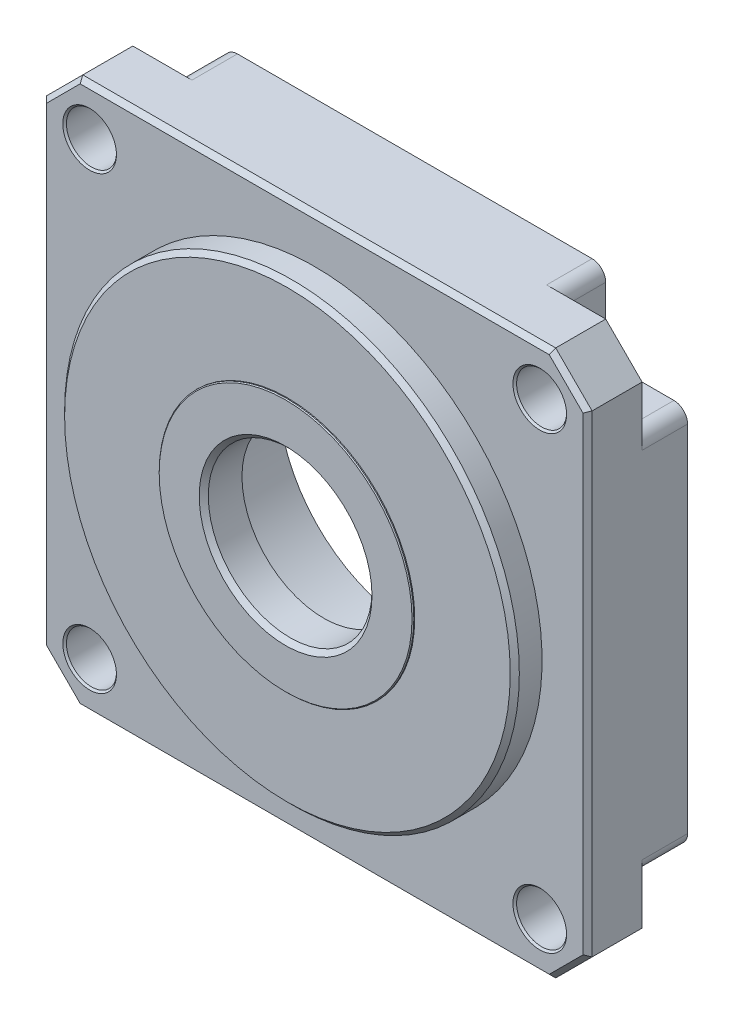
SolidWorks part; units mm, degrees
material "6061 Alloy"
ref_plane "Front Plane" through (0, 0, 0) normal (0, 0, 1) x (1, 0, 0)
ref_plane "Top Plane" through (0, 0, 0) normal (0, 1, 0) x (1, 0, 0)
ref_plane "Right Plane" through (0, 0, 0) normal (1, 0, 0) x (0, 0, -1)
sketch "Sketch1" plane through (0, 0, 0) normal (0, 0, 1) x (1, 0, 0)
  line L0 (30, 0) -> (30, 60) construction
  line L1 (0, 0) -> (60, 0)
  line L2 (0, 0) -> (0, 60)
  line L3 (0, 60) -> (60, 60)
  line L4 (60, 0) -> (60, 60)
  line L5 (0, 30) -> (60, 30) construction
  circle A0 centre (30, 30) radius 9
  dimension "D1" = 60
  dimension "D2" = 60
extrude "Boss-Extrude1" add sketch "Sketch1" along normal blind 11
sketch "Sketch2" plane through (0, 0, 11) normal (0, 0, 1) x (1, 0, 0)
  circle A0 centre (30, 30) radius 25
  circle A1 centre (30, 30) radius 9
extrude "Boss-Extrude2" add sketch "Sketch2" along normal blind 3
sketch "Sketch3" plane through (0, 0, 14) normal (0, 0, 1) x (1, 0, 0)
  circle A0 centre (30, 30) radius 14
  circle A1 centre (30, 30) radius 9
extrude "Boss-Extrude3" add sketch "Sketch3" along normal blind 0.2
chamfer "Chamfer1" distance 0.5 angle 45 1 edges at (55, 30, 14)
chamfer "Chamfer2" distance 0.5 angle 45 1 edges at (39, 30, 14.2)
hole_wizard "Ø5.5 (5.5) Diameter Hole1" positions "Sketch5" profile "Sketch4" hole size "Ø5.5" standard "ANSI Metric" end condition through all
sketch "Sketch5" plane through (0, 0, 11) normal (0, 0, 1) x (1, 0, 0)
  line L0 (30, 30) -> (0, 60) construction
  circle A0 centre (30, 30) radius 35
  point P0 (5.2513, 54.7487)
sketch "Sketch4" plane through (5.2513, 54.7487, 11) normal (1, 0, 0) x (0, -1, 0)
  line L0 (0, 0) -> (0, 11)
  line L1 (0, 11) -> (2.75, 11)
  line L2 (2.75, 11) -> (2.75, 0)
  line L5 (2.75, 0) -> (0, 0)
  line L11 (0, -6.35) -> (0, 107.95) construction
  dimension "Thru Hole Dia." = 5.5
  dimension "Thru Hole Depth" = 11
pattern_circular "CirPattern1" count 4 every 90 about axis through (30, 30, 0) along (0, 0, 1) of "Ø5.5 (5.5) Diameter Hole1"
chamfer "Chamfer3" distance 4 angle 45 1 edges at (0, 60, 5.5)
chamfer "Chamfer4" distance 4 angle 45 1 edges at (60, 60, 5.5)
chamfer "Chamfer5" distance 4 angle 45 1 edges at (60, 0, 5.5)
chamfer "Chamfer6" distance 4 angle 45 1 edges at (0, 0, 5.5)
sketch "Sketch6" plane through (0, 0, 0) normal (0, 0, -1) x (-1, 0, 0)
  line L0 (-30, 30) -> (3.0729, 63.0729) construction
  line L1 (0, 56) -> (0, 4) construction
  line L2 (-9, 68.3378) -> (7.3063, 68.3378)
  line L3 (-9, 68.3378) -> (-9, 55)
  line L4 (-5, 51) -> (7.3063, 51)
  line L5 (7.3063, 68.3378) -> (7.3063, 51)
  line L6 (-56, 60) -> (-4, 60) construction
  line L7 (8.3378, 9) -> (8.3378, -7.3063)
  line L8 (8.3378, 9) -> (-5, 9)
  line L9 (-9, 5) -> (-9, -7.3063)
  line L10 (8.3378, -7.3063) -> (-9, -7.3063)
  line L11 (-51, -8.3378) -> (-67.3063, -8.3378)
  line L12 (-51, -8.3378) -> (-51, 5)
  line L13 (-55, 9) -> (-67.3063, 9)
  line L14 (-67.3063, -8.3378) -> (-67.3063, 9)
  line L15 (-68.3378, 51) -> (-68.3378, 67.3063)
  line L16 (-68.3378, 51) -> (-55, 51)
  line L17 (-51, 55) -> (-51, 67.3063)
  line L18 (-68.3378, 67.3063) -> (-51, 67.3063)
  arc A0 (-9, 55) -> (-5, 51) centre (-5, 55) ccw
  arc A1 (-5, 9) -> (-9, 5) centre (-5, 5) ccw
  arc A2 (-51, 5) -> (-55, 9) centre (-55, 5) ccw
  arc A3 (-55, 51) -> (-51, 55) centre (-55, 55) ccw
  point P34 (-30, 30)
  dimension "D1" = 9
  dimension "D3" = 4
  dimension "D2" = 9
  dimension "D4" = 4
extrude "Cut-Extrude1" cut sketch "Sketch6" against normal blind 5
fillet "Fillet3" radius 1.5 1 edges at (60, 51, 2.5)
fillet "Fillet4" radius 1.5 1 edges at (51, 60, 2.5)
fillet "Fillet5" radius 1.5 6 edges at (60, 9, 2.5) (51, 0, 2.5) (9, 0, 2.5) (0, 9, 2.5) (0, 51, 2.5) (9, 60, 2.5)
chamfer "Chamfer7" distance 0.5 angle 45 8 edges at (2, 2, 11) (0, 30, 11) (2, 58, 11) (30, 60, 11) (58, 58, 11) (60, 30, 11) (58, 2, 11) (30, 0, 11)
chamfer "Chamfer8" distance 0.2 angle 45 4 edges at (8.0013, 5.2513, 11) (8.0013, 54.7487, 11) (57.4987, 54.7487, 11) (57.4987, 5.2513, 11)
chamfer "Chamfer9" distance 0.1 angle 45 1 edges at (44, 30, 14.2)
chamfer "Chamfer10" distance 0.5 angle 45 1 edges at (39, 30, 0)
sketch "Sketch7" plane through (0, 0, 0) normal (0, 0, -1) x (-1, 0, 0)
  circle A0 centre (-30, 30) radius 15
extrude "Cut-Extrude2" cut sketch "Sketch7" against normal blind 10
scale "Scale1" scale about centroid uniform scaling yes scale factor 2.3
